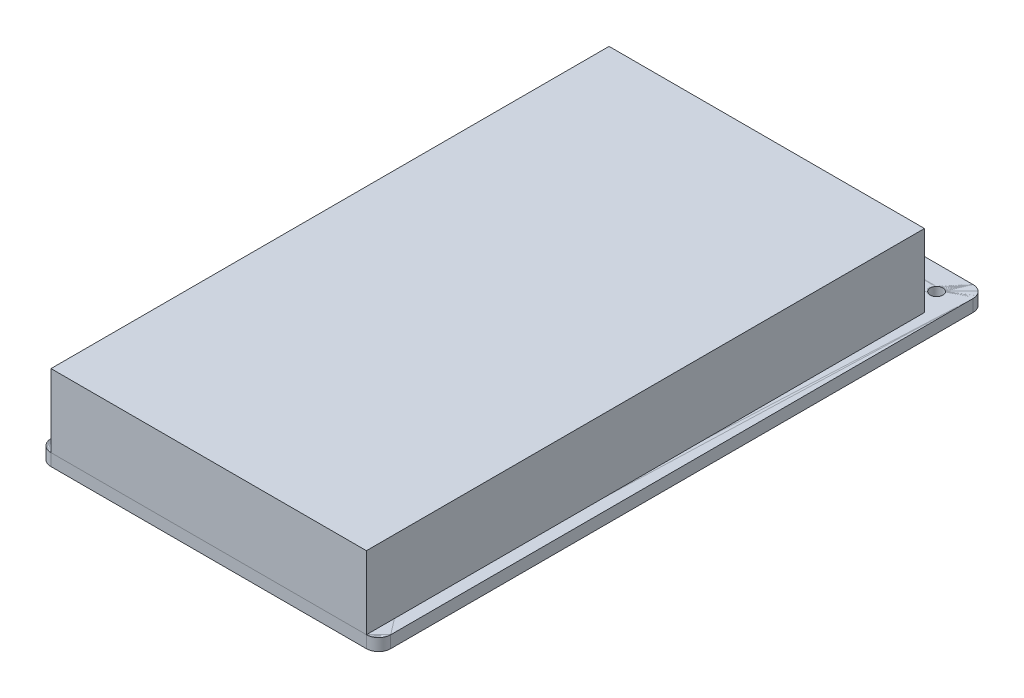
SolidWorks part; units mm, degrees
material "Balsa"
ref_plane "Front Plane" through (0, 0, 0) normal (0, 0, 1) x (1, 0, 0)
ref_plane "Top Plane" through (0, 0, 0) normal (0, 1, 0) x (1, 0, 0)
ref_plane "Right Plane" through (0, 0, 0) normal (1, 0, 0) x (0, 0, -1)
sketch "Sketch1" plane through (0, 0, 0) normal (0, 1, 0) x (1, 0, 0)
  line L1 (-88.9, 158.75) -> (88.9, 158.75)
  line L2 (-88.9, 158.75) -> (-88.9, -158.75)
  line L3 (-88.9, -158.75) -> (88.9, -158.75)
  line L4 (88.9, 158.75) -> (88.9, -158.75)
  line L5 (-88.9, 158.75) -> (88.9, -158.75) construction
  line L6 (-88.9, -158.75) -> (88.9, 158.75) construction
  point P0 (0, 0)
  dimension "D1" = 177.8
  dimension "D2" = 317.5
extrude "Base" add sketch "Sketch1" along normal blind 6.35
sketch "Sketch3" plane through (0, 0, 0) normal (0, -1, 0) x (1, 0, 0)
  line L5 (88.9, -158.75) -> (-88.9, -158.75) construction
  line L8 (-76.2, 133.35) -> (76.2, 133.35) construction
  line L9 (-76.2, 133.35) -> (-76.2, -146.05) construction
  line L10 (-76.2, -146.05) -> (76.2, -146.05) construction
  line L11 (76.2, 133.35) -> (76.2, -146.05) construction
  line L12 (0, -146.05) -> (0, 133.35) construction
  line L13 (-76.2, -6.35) -> (76.2, -6.35) construction
  line L14 (88.9, 158.75) -> (88.9, -158.75) construction
  line L15 (-88.9, 158.75) -> (88.9, 158.75) construction
  circle A4 centre (-76.2, -146.05) radius 3.302
  circle A5 centre (76.2, -146.05) radius 3.302
  circle A6 centre (76.2, 133.35) radius 3.302
  circle A7 centre (-76.2, 133.35) radius 3.302
  point P258 (0, -6.35)
  dimension "D3" = 6.604
  dimension "D1" = 12.7
  dimension "D2" = 12.7
  dimension "D4" = 25.4
extrude "Holes" cut sketch "Sketch3" against normal through all both and the other way through all
sketch "Sketch6" plane through (0, 0, 0) normal (0, -1, 0) x (1, 0, 0)
  line L5 (-76.2, 133.35) -> (-76.2, -146.05) construction
  line L6 (-76.2, 133.35) -> (76.2, 133.35) construction
  line L8 (0, -921.4775) -> (0, 49078.5225) construction
  line L10 (-963.0198, -6.35) -> (49036.9802, -6.35) construction
  line L12 (0, -146.05) -> (0, 133.35) construction
  line L13 (-76.2, -6.35) -> (76.2, -6.35) construction
  line L14 (-76.2, 120.65) -> (-76.2, -133.35)
  line L15 (-63.5, 133.35) -> (63.5, 133.35)
  line L16 (76.2, 120.65) -> (76.2, -133.35)
  line L17 (-63.5, -146.05) -> (63.5, -146.05)
  arc A0 (-76.2, 120.65) -> (-63.5, 133.35) centre (-76.2, 133.35) ccw
  arc A1 (76.2, 120.65) -> (63.5, 133.35) centre (76.2, 133.35) cw
  arc A2 (76.2, -133.35) -> (63.5, -146.05) centre (76.2, -146.05) ccw
  arc A3 (-76.2, -133.35) -> (-63.5, -146.05) centre (-76.2, -146.05) cw
  point P17 (0, -146.05)
  point P20 (-76.2, -6.35)
  point P24 (0, 133.35)
  point P31 (76.2, -6.35)
  dimension "D1" = 12.7
extrude "Inner Cutout" cut sketch "Sketch6" against normal through all both and the other way through all
fillet "Fillet1" radius 6.35 12 edges at (-88.9, 3.175, -158.75) (88.9, 3.175, -158.75) (88.9, 3.175, 158.75) (-88.9, 3.175, 158.75) (76.2, 3.175, 120.65) (63.5, 3.175, 133.35) (-63.5, 3.175, 133.35) (-76.2, 3.175, 120.65) (-76.2, 3.175, -133.35) (-63.5, 3.175, -146.05) (76.2, 3.175, -133.35) (63.5, 3.175, -146.05)
sketch "Sketch7" plane through (0, 6.35, 0) normal (0, 1, 0) x (1, 0, 0)
  line L4 (82.55, 158.75) -> (-82.55, 158.75)
  line L5 (-88.9, 152.4) -> (-88.9, -152.4)
  line L6 (-82.55, -158.75) -> (82.55, -158.75)
  line L7 (88.9, -152.4) -> (88.9, 152.4)
  line L8 (82.55, 158.75) -> (-82.55, 158.75)
  line L9 (-88.9, 152.4) -> (-88.9, -152.4)
  line L10 (-82.55, -158.75) -> (82.55, -158.75)
  line L11 (88.9, -152.4) -> (88.9, 152.4)
  circle A0 centre (-76.2, -133.35) radius 3.302 construction
  circle A1 centre (76.2, -133.35) radius 3.302 construction
  circle A2 centre (-76.2, 146.05) radius 3.302 construction
  circle A3 centre (76.2, 146.05) radius 3.302 construction
  arc A4 (-82.55, 158.75) -> (-88.9, 152.4) centre (-82.55, 152.4) ccw
  arc A5 (-88.9, -152.4) -> (-82.55, -158.75) centre (-82.55, -152.4) ccw
  arc A6 (82.55, -158.75) -> (88.9, -152.4) centre (82.55, -152.4) ccw
  arc A7 (88.9, 152.4) -> (82.55, 158.75) centre (82.55, 152.4) ccw
  arc A8 (-82.55, 158.75) -> (-88.9, 152.4) centre (-82.55, 152.4) ccw
  arc A9 (-88.9, -152.4) -> (-82.55, -158.75) centre (-82.55, -152.4) ccw
  arc A10 (82.55, -158.75) -> (88.9, -152.4) centre (82.55, -152.4) ccw
  arc A11 (88.9, 152.4) -> (82.55, 158.75) centre (82.55, 152.4) ccw
  circle A12 centre (-76.2, -133.35) radius 3.302
  circle A13 centre (76.2, -133.35) radius 3.302
  circle A14 centre (-76.2, 146.05) radius 3.302
  circle A15 centre (76.2, 146.05) radius 3.302
  dimension "D1" = 0
surface "Surface-Plane1" sketch "Sketch7"
sketch "Sketch8" plane through (0, 0, 0) normal (0, -1, 0) x (1, 0, 0)
  line L4 (88.9, -152.4) -> (88.9, 152.4)
  line L5 (82.55, 158.75) -> (-82.55, 158.75)
  line L6 (-88.9, 152.4) -> (-88.9, -152.4)
  line L7 (-82.55, -158.75) -> (82.55, -158.75)
  line L8 (88.9, -152.4) -> (88.9, 152.4)
  line L9 (82.55, 158.75) -> (-82.55, 158.75)
  line L10 (-88.9, 152.4) -> (-88.9, -152.4)
  line L11 (-82.55, -158.75) -> (82.55, -158.75)
  circle A1 centre (76.2, -146.05) radius 3.302
  circle A2 centre (76.2, -146.05) radius 3.302
  circle A3 centre (-76.2, -146.05) radius 3.302
  circle A4 centre (-76.2, -146.05) radius 3.302
  circle A5 centre (76.2, 133.35) radius 3.302
  circle A6 centre (76.2, 133.35) radius 3.302
  circle A7 centre (-76.2, 133.35) radius 3.302
  circle A8 centre (-76.2, 133.35) radius 3.302
  arc A12 (88.9, 152.4) -> (82.55, 158.75) centre (82.55, 152.4) ccw
  arc A13 (-82.55, 158.75) -> (-88.9, 152.4) centre (-82.55, 152.4) ccw
  arc A14 (-88.9, -152.4) -> (-82.55, -158.75) centre (-82.55, -152.4) ccw
  arc A15 (82.55, -158.75) -> (88.9, -152.4) centre (82.55, -152.4) ccw
  arc A16 (88.9, 152.4) -> (82.55, 158.75) centre (82.55, 152.4) ccw
  arc A17 (-82.55, 158.75) -> (-88.9, 152.4) centre (-82.55, 152.4) ccw
  arc A18 (-88.9, -152.4) -> (-82.55, -158.75) centre (-82.55, -152.4) ccw
  arc A19 (82.55, -158.75) -> (88.9, -152.4) centre (82.55, -152.4) ccw
  dimension "D1" = 0
  dimension "D2" = 0
  dimension "D3" = 0
  dimension "D4" = 0
  dimension "D5" = 0
surface "Surface-Plane2" sketch "Sketch8"
sketch "Sketch2" plane through (0, 6.35, 0) normal (0, 1, 0) x (1, 0, 0)
  line L0 (-82.55, -158.75) -> (82.55, -158.75) construction
  line L5 (-82.55, -158.75) -> (82.55, -158.75)
  line L6 (-82.55, -158.75) -> (-82.55, 133.35)
  line L7 (-82.55, 133.35) -> (82.55, 133.35)
  line L8 (82.55, -158.75) -> (82.55, 133.35)
  line L9 (0, 133.35) -> (0, -158.75) construction
  line L10 (-82.55, -12.7) -> (82.55, -12.7) construction
  point P334 (0, -12.7)
  dimension "D1" = 292.1
  dimension "D2" = 165.1
extrude "Padding" add sketch "Sketch2" along normal blind 38.1 separate body
